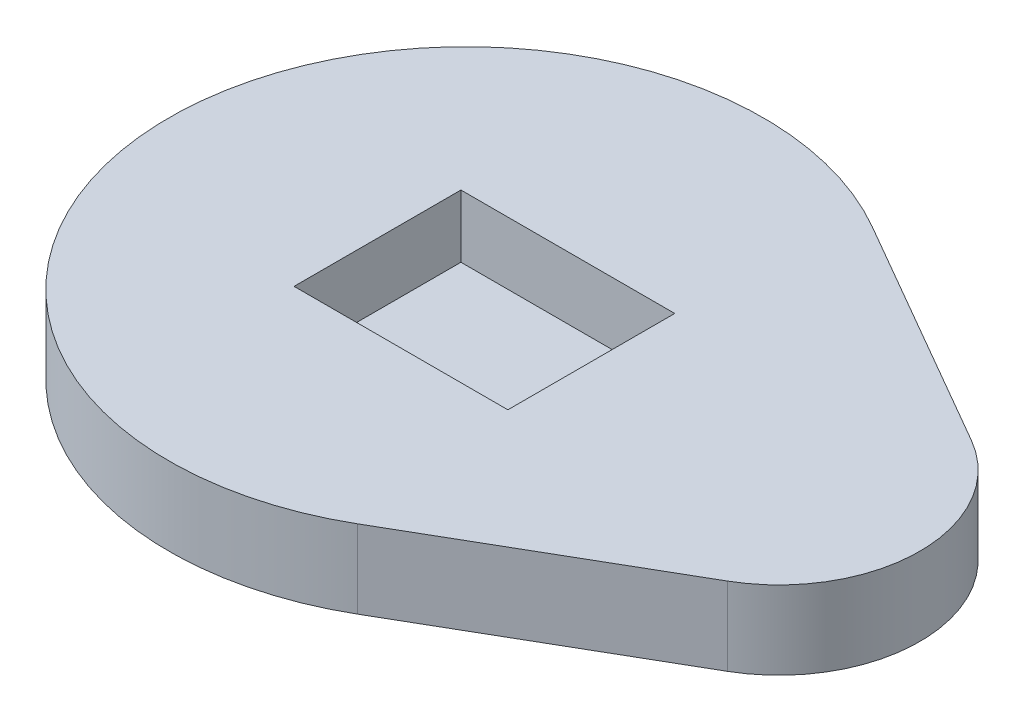
SolidWorks part; units mm, degrees
ref_plane "Front Plane" through (0, 0, 0) normal (0, 0, 1) x (1, 0, 0)
ref_plane "Top Plane" through (0, 0, 0) normal (0, 1, 0) x (1, 0, 0)
ref_plane "Right Plane" through (0, 0, 0) normal (1, 0, 0) x (0, 0, -1)
sketch "Sketch1" plane through (0, 0, 0) normal (0, 1, 0) x (1, 0, 0)
  line L9 (13.5, -49.3634) -> (58.5, -23.3827)
  line L10 (13.5, 49.3634) -> (58.5, 23.3827)
  circle A0 centre (-15, 0) radius 46.5 construction
  circle A1 centre (45, 0) radius 16.5 construction
  circle A8 centre (-15, 0) radius 57 construction
  circle A9 centre (45, 0) radius 27 construction
  arc A12 (13.5, 49.3634) -> (13.5, -49.3634) centre (-15, 0) ccw
  arc A13 (58.5, 23.3827) -> (58.5, -23.3827) centre (45, 0) cw
  point P17 (45, 0)
  point P18 (45, 0)
extrude "Boss-Extrude1" add sketch "Sketch1" along normal blind 15
sketch "Sketch2" plane through (0, 15, 0) normal (0, 1, 0) x (1, 0, 0)
  line L0 (-15, 0) -> (-32, 0) construction
  line L1 (-15, 0) -> (9, 0) construction
  line L2 (-15, -16) -> (-15, 16) construction
  line L3 (-32, -16) -> (-32, 16)
  line L4 (-32, 16) -> (9, 16)
  line L5 (9, 16) -> (9, -16)
  line L6 (9, -16) -> (-32, -16)
  point P8 (-15, 0)
  point P11 (-32, 0)
extrude "Cut-Extrude1" cut sketch "Sketch2" against normal blind 12
